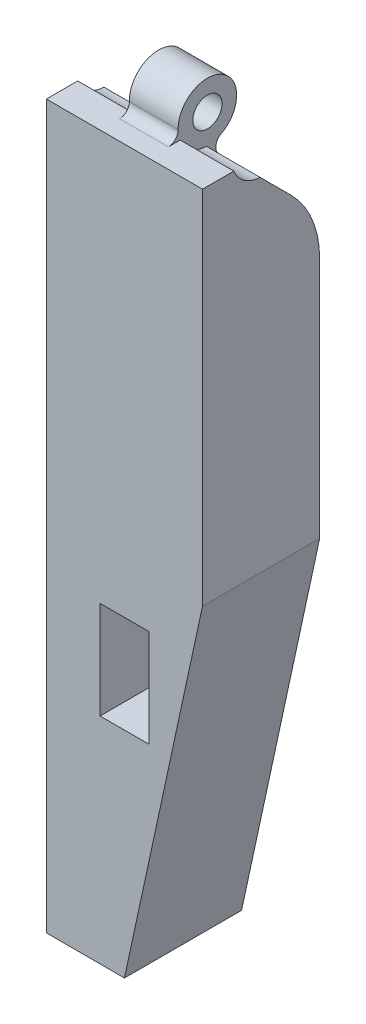
SolidWorks part; units mm, degrees
ref_plane "Front Plane" through (0, 0, 0) normal (0, 0, 1) x (1, 0, 0)
ref_plane "Top Plane" through (0, 0, 0) normal (0, 1, 0) x (1, 0, 0)
ref_plane "Right Plane" through (0, 0, 0) normal (1, 0, 0) x (0, 0, -1)
sketch "Sketch1" plane through (0, 0, 0) normal (0, 0, 1) x (1, 0, 0)
  line L0 (0, 26.1328) -> (0, -47.8672)
  line L1 (0, 26.1328) -> (16, 26.1328)
  line L2 (16, 26.1328) -> (16, -10.8672)
  line L3 (0, -47.8672) -> (8, -47.8672)
  line L4 (8, -47.8672) -> (16, -10.8672)
extrude "Boss-Extrude1" add sketch "Sketch1" along normal blind 12
sketch "Sketch2" plane through (0, 26.1328, 0) normal (0, 1, 0) x (1, 0, 0)
  line L0 (8, 0) -> (8, -12)
  line L1 (16, 0) -> (0, 0) construction
ref_plane "Plane1" through (8, 0, 0) normal (1, 0, 0) x (0, 0, -1)
sketch "Sketch3" plane through (8, 0, 0) normal (1, 0, 0) x (0, 0, -1)
  line L0 (-8, 26.1328) -> (0, 26.1328)
  line L1 (0, 26.1328) -> (-12, 26.1328) construction
  line L2 (0, -10.8672) -> (0, 26.1328) construction
  line L7 (-8, 26.1328) -> (0, 18.1328)
  line L8 (0, 18.1328) -> (0, 26.1328)
extrude "Cut-Extrude1" cut sketch "Sketch3" against normal through all both and the other way through all
sketch "Sketch4" plane through (8, 0, 0) normal (1, 0, 0) x (0, 0, -1)
  line L0 (-6, 26.1328) -> (-6, 27.2328)
  line L1 (0, 26.1328) -> (-12, 26.1328) construction
  circle A0 centre (-6, 27.2328) radius 1.5
  circle A1 centre (-6, 27.2328) radius 3
extrude "Cut-Extrude2" cut sketch "Sketch4" against normal through all both and the other way through all contours A1 A0
sketch "Sketch5" plane through (8, 0, 0) normal (1, 0, 0) x (0, 0, -1)
  circle A0 centre (-6, 27.2328) radius 1.5
  circle A1 centre (-6, 27.2328) radius 3
extrude "Boss-Extrude2" add sketch "Sketch5" along normal mid plane 5
fillet "Fillet1" radius 1 2 edges at (8, 26.1328, 8.7911) (8, 24.2345, 6.1017)
fillet "Fillet2" radius 10 1 edges at (8, 18.1328, 0)
sketch "Sketch6" plane through (0, 0, 0) normal (0, 0, -1) x (-1, 0, 0)
  line L0 (-16, -10.8672) -> (0, -10.8672)
  line L1 (0, 13.9907) -> (0, -47.8672) construction
  line L3 (-10.5, -5.8672) -> (-5.5, -5.8672)
  line L4 (-10.5, -5.8672) -> (-10.5, -15.8672)
  line L5 (-10.5, -15.8672) -> (-5.5, -15.8672)
  line L6 (-5.5, -5.8672) -> (-5.5, -15.8672)
  line L7 (-10.5, -5.8672) -> (-5.5, -15.8672) construction
  line L8 (-10.5, -15.8672) -> (-5.5, -5.8672) construction
  line L9 (-10.5, -15.8672) -> (-5.5, -15.8672)
  line L10 (-10.5, -15.8672) -> (-10.5, -25.8672)
  line L11 (-10.5, -25.8672) -> (-5.5, -25.8672)
  line L12 (-5.5, -15.8672) -> (-5.5, -25.8672)
  line L13 (-10.5, -5.8672) -> (-5.5, -5.8672)
  line L14 (-10.5, -5.8672) -> (-10.5, 4.1328)
  line L15 (-10.5, 4.1328) -> (-5.5, 4.1328)
  line L16 (-5.5, -5.8672) -> (-5.5, 4.1328)
  point P5 (-8, -10.8672)
extrude "Cut-Extrude3" cut sketch "Sketch6" against normal blind 5 contours L3 L16 L15 L14 | L12 L5 L10 L11
sketch "Sketch7" plane through (0, -15.8672, 0) normal (0, -1, 0) x (1, 0, 0)
  line L0 (10.5, 5) -> (10.5, 0) construction
  line L1 (5.5, 5) -> (10.5, 5)
  line L2 (5.5, 5) -> (5.5, 2.5)
  line L3 (5.5, 2.5) -> (10.5, 2.5)
  line L4 (10.5, 5) -> (10.5, 2.5)
extrude "Cut-Extrude4" cut sketch "Sketch7" against normal up to surface (10 mm away) up to face at (8, -5.8672, 2.5)
sketch "Sketch8" plane through (0, 0, 0) normal (0, 0, -1) x (-1, 0, 0)
  line L1 (-10.5, -15.8672) -> (-5.5, -15.8672)
  line L2 (-10.5, -15.8672) -> (-10.5, -25.8672)
  line L3 (-10.5, -25.8672) -> (-5.5, -25.8672)
  line L4 (-5.5, -15.8672) -> (-5.5, -25.8672)
extrude "Cut-Extrude5" cut sketch "Sketch8" against normal through all
